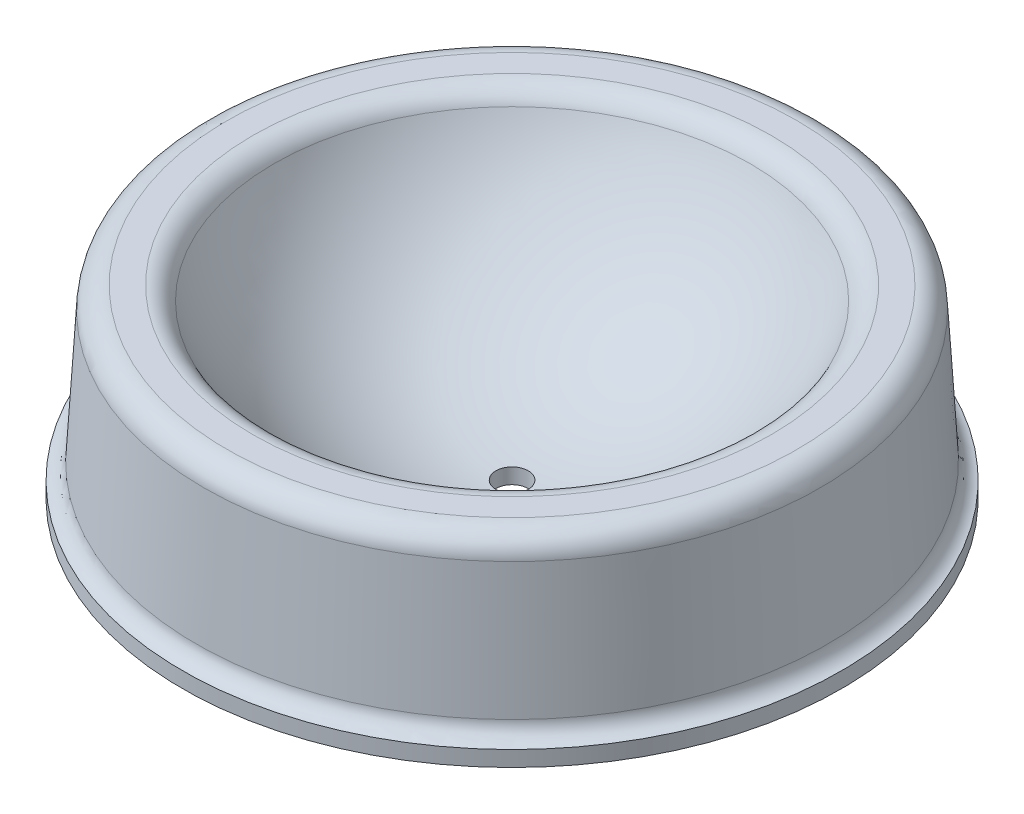
SolidWorks part; units mm, degrees
material "Plain Carbon Steel"
ref_plane "Front Plane" through (0, 0, 0) normal (0, 0, 1) x (1, 0, 0)
ref_plane "Top Plane" through (0, 0, 0) normal (0, 1, 0) x (1, 0, 0)
ref_plane "Right Plane" through (0, 0, 0) normal (1, 0, 0) x (0, 0, -1)
sketch "Sketch1" plane through (0, 0, 0) normal (0, 0, 1) x (1, 0, 0)
  line L0 (19.5, 2) -> (19, 10.5293)
  line L1 (18.5009, 11) -> (16.83, 11)
  line L2 (0, 0) -> (0, 17.875) construction
  line L3 (0, 0) -> (21.4, 0) construction
  line L4 (21.4, 0) -> (0, 0) construction
  line L5 (20.4983, 2.0585) -> (19.9983, 10.5878)
  line L6 (18.5009, 12) -> (16.83, 12)
  line L7 (0, 0) -> (0, 1)
  line L8 (21.4, 0) -> (21.4, 1.0115)
  arc A0 (16.3721, 10.7007) -> (0, 0) centre (0, 17.875) cw
  arc A1 (19.5, 2) -> (21.4, 0) centre (21.6343, 2.1251) ccw
  arc A2 (19, 10.5293) -> (18.5009, 11) centre (18.5009, 10.5) ccw
  arc A3 (16.83, 11) -> (16.3721, 10.7007) centre (16.83, 10.5) ccw
  arc A4 (20.4983, 2.0585) -> (21.4, 1.0115) centre (21.6343, 2.1251) ccw
  arc A5 (19.9983, 10.5878) -> (18.5009, 12) centre (18.5009, 10.5) ccw
  arc A6 (16.83, 12) -> (15.4562, 11.102) centre (16.83, 10.5) ccw
  arc A7 (15.4562, 11.102) -> (0, 1) centre (0, 17.875) cw
  arc A9 (20.4983, 2.0585) -> (21.5096, 0.994) centre (21.6343, 2.1251) ccw construction
  point P13 (16.5, 11)
  dimension "D6" = 0.5
  dimension "D8" = 2.138
  dimension "D1" = 21.4
  dimension "D2" = 0.5
  dimension "D3" = 2
  dimension "D4" = 16.5
  dimension "D5" = 11
  dimension "D7" = 19
  dimension "D9" = 19
  dimension "D11" = 1.6708
  dimension "D10" = 1
revolve "MAIN BODY" add sketch "Sketch1" angle 360 about L2
sketch "Sketch2" plane through (0, 0, 0) normal (0, 1, 0) x (1, 0, 0)
  circle A0 centre (0, 0) radius 1.05
  dimension "D1" = 2.1
extrude "HOLE IN BASE" cut sketch "Sketch2" along normal up to next
